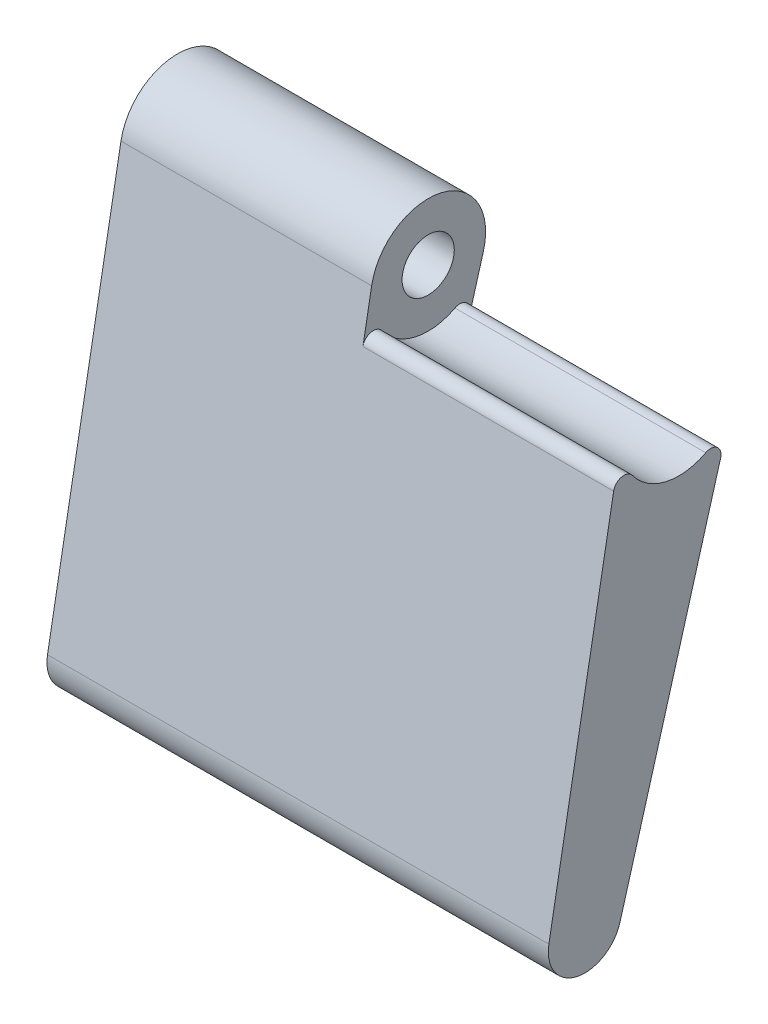
SolidWorks part; units mm, degrees
ref_plane "前视基准面" through (0, 0, 0) normal (0, 0, 1) x (1, 0, 0)
ref_plane "上视基准面" through (0, 0, 0) normal (0, 1, 0) x (1, 0, 0)
ref_plane "右视基准面" through (0, 0, 0) normal (1, 0, 0) x (0, 0, -1)
sketch "草图1" plane through (63.25, 0, 0) normal (1, 0, 0) x (0, 0, -1)
  line L1 (-77.1781, -53.7033) -> (-79.9088, -63.2457)
  line L2 (-81.6112, -62.85) -> (-79.8533, -53.0815)
  circle A0 centre (-78.5, -53.325) radius 0.625
  circle A1 centre (-78.5, -53.325) radius 1.375
  circle A2 centre (-80.75, -63.005) radius 0.875
  arc A3 (-79.3564, -52.2493) -> (-77.7642, -54.4866) centre (-78.5, -53.325) ccw construction
  circle M2 centre (-78.5, -53.325) radius 0.625
  line M4 (-66.1813, -39.4809) -> (-79.3564, -52.2493)
  arc M5 (-79.3564, -52.2493) -> (-77.7642, -54.4866) centre (-78.5, -53.325) ccw
  line M6 (-77.7642, -54.4866) -> (-62.7665, -44.9867)
  dimension "D2" = 1.75
  dimension "D1" = 2.25
  dimension "D3" = 9.68
extrude "凸台-拉伸1" add sketch "草图1" against normal up to surface (12 mm away) contours A1 M6 M4 M5 M2 | A2 | A2 L1 A1 L2 M6 | A1 L1 M6
sketch "草图2" plane through (63.25, 0, 0) normal (1, 0, 0) x (0, 0, -1)
  circle A0 centre (-78.5, -53.325) radius 1.375
extrude "切除-拉伸1" cut sketch "草图2" against normal up to surface (6 mm away)
sketch "草图3" plane through (63.25, 0, 0) normal (1, 0, 0) x (0, 0, -1)
  line L1 (-80.4984, -52.8024) -> (-79.2889, -52.8024)
  line L2 (-79.8533, -53.0815) -> (-81.6112, -62.85)
  line L3 (-79.9088, -63.2457) -> (-77.1781, -53.7033)
  line L4 (-80.0609, -54.2355) -> (-81.6112, -62.85)
  line L5 (-79.9088, -63.2457) -> (-77.1781, -53.7033)
  line L6 (-80.4984, -52.8024) -> (-80.4984, -54.3645)
  line L7 (-80.4984, -54.3645) -> (-79.2889, -54.3645)
  line L8 (-79.2889, -52.8024) -> (-79.2889, -54.3645)
  line L9 (-78.1006, -53.325) -> (-76.6443, -53.325)
  line L10 (-78.1006, -53.325) -> (-78.1006, -55.4717)
  line L11 (-78.1006, -55.4717) -> (-76.6443, -55.4717)
  line L12 (-76.6443, -53.325) -> (-76.6443, -55.4717)
  arc A0 (-79.6126, -54.1329) -> (-80.0609, -54.2355) centre (-79.8149, -54.2798) ccw
  circle A1 centre (-77.741, -54.7619) radius 0.25
  arc A2 (-79.8533, -53.0815) -> (-77.1781, -53.7033) centre (-78.5, -53.325) ccw
  arc A3 (-81.6112, -62.85) -> (-79.9088, -63.2457) centre (-80.75, -63.005) ccw
  arc A4 (-79.6126, -54.1329) -> (-77.1781, -53.7033) centre (-78.5, -53.325) ccw
  arc A5 (-81.6112, -62.85) -> (-79.9088, -63.2457) centre (-80.75, -63.005) ccw
  arc M15 (-77.1781, -53.7033) -> (-79.8533, -53.0815) centre (-78.5, -53.325) cw
  line M16 (-79.8533, -53.0815) -> (-81.6112, -62.85)
  line M18 (-79.9088, -63.2457) -> (-77.1781, -53.7033)
  dimension "D2" = 0.25
  dimension "D3" = 0.5
  dimension "D1" = 0
extrude "切除-拉伸2" cut sketch "草图3" against normal up to surface (6 mm away) contours L8 L1 L6 L7 M16 M15 | A0 M15 M16 | L12 L9 L10 L5 L11 M15 M18 | A1 M18 M15
